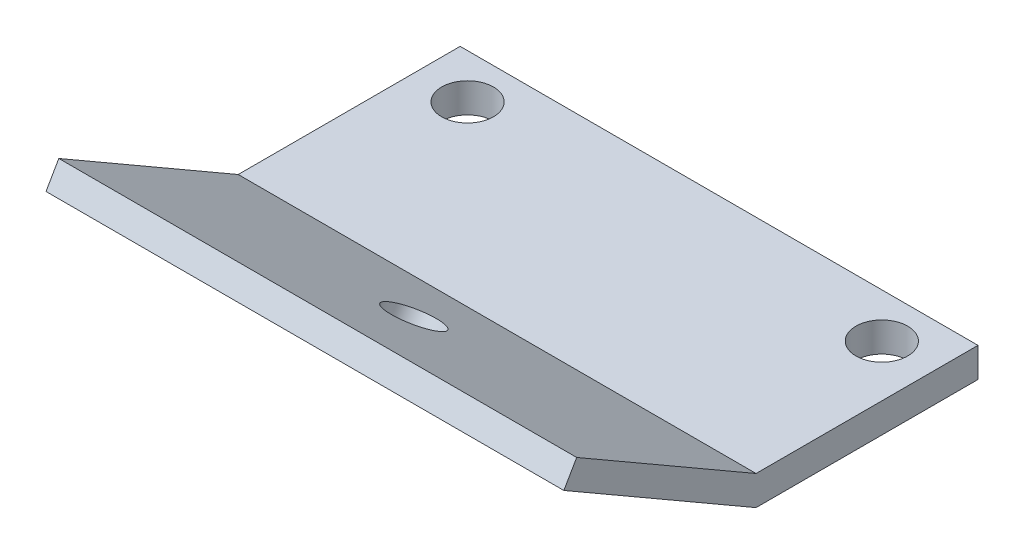
SolidWorks part; units mm, degrees
ref_plane "Front" through (0, 0, 0) normal (0, 0, 1) x (1, 0, 0)
ref_plane "Top" through (0, 0, 0) normal (0, 1, 0) x (1, 0, 0)
ref_plane "Right" through (0, 0, 0) normal (1, 0, 0) x (0, 0, -1)
sketch "Croquis1" plane through (0, 0, 0) normal (0, 1, 0) x (1, 0, 0)
  line L0 (-1000, 4.5) -> (49000, 4.5) construction
  line L1 (-17.5, -7.5) -> (17.5, -7.5)
  line L2 (-17.5, -7.5) -> (-17.5, 7.5)
  line L3 (-17.5, 7.5) -> (17.5, 7.5)
  line L4 (17.5, -7.5) -> (17.5, 7.5)
  line L5 (-17.5, -7.5) -> (17.5, 7.5) construction
  line L6 (-17.5, 7.5) -> (17.5, -7.5) construction
  line L7 (0, -1000) -> (0, 49000) construction
  circle A0 centre (-14, 4.5) radius 1.75 construction
  circle A1 centre (14, 4.5) radius 1.75 construction
  point P0 (0, 0)
  dimension "D3" = 3.5
  dimension "D4" = 14
  dimension "D5" = 3
  dimension "D1" = 35
  dimension "D2" = 15
extrude "Saliente-Extruir1" add sketch "Croquis1" along normal blind 2
sketch "Croquis2" plane through (0, 2, 0) normal (0, 1, 0) x (1, 0, 0)
  line L0 (-1016.9104, 4.5) -> (48983.0896, 4.5) construction
  circle A0 centre (-14, 4.5) radius 1.75
  circle A1 centre (14, 4.5) radius 1.75
extrude "Cortar-Extruir1" cut sketch "Croquis2" against normal through all
ref_plane "Plano1" through (0, 3.2476, 5.625) normal (0, 0.5, 0.866) x (1, 0, 0)
sketch "Croquis3" plane through (0, 3.2476, 5.625) normal (0, 0.5, 0.866) x (1, 0, 0)
  line L1 (-17.5, -3.75) -> (17.5, -3.75)
  line L2 (-17.5, -3.75) -> (-17.5, -2.0179)
  line L3 (-17.5, -2.0179) -> (17.5, -2.0179)
  line L4 (17.5, -3.75) -> (17.5, -2.0179)
extrude "Saliente-Extruir2" add sketch "Croquis3" along normal blind 15
sketch "Croquis4" plane through (0, -3.2476, 1.875) normal (0, -0.866, 0.5) x (1, 0, 0)
  line L0 (17.5, 21.4952) -> (-17.5, 6.4952) construction
  line L1 (2.9168, 6.4952) -> (-2.9168, 6.4952) construction
  line L2 (-17.5, -6.4952) -> (-17.5, 6.4952) construction
  line L3 (-17.5, 21.4952) -> (17.5, 6.4952) construction
  circle A0 centre (0, 13.9952) radius 1.75
  dimension "D1" = 3.5
extrude "Cortar-Extruir2" cut sketch "Croquis4" against normal up to next
